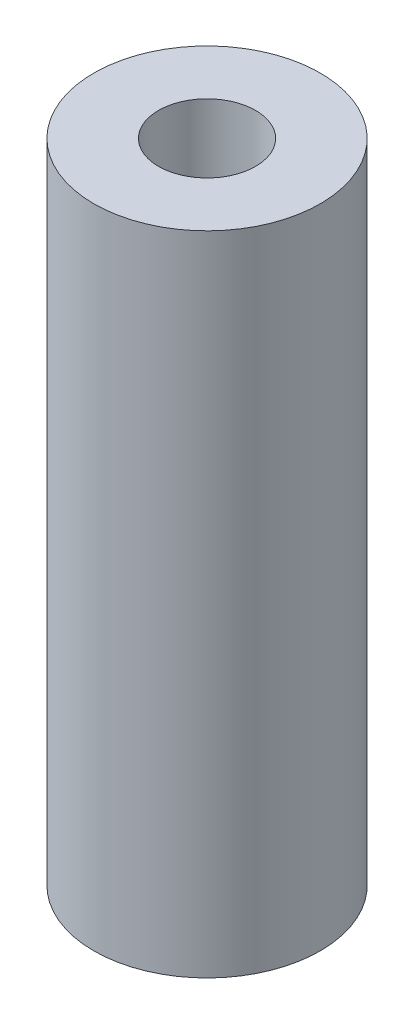
SolidWorks part; units mm, degrees
ref_plane "Front Plane" through (0, 0, 0) normal (0, 0, 1) x (1, 0, 0)
ref_plane "Top Plane" through (0, 0, 0) normal (0, 1, 0) x (1, 0, 0)
ref_plane "Right Plane" through (0, 0, 0) normal (1, 0, 0) x (0, 0, -1)
sketch "Sketch1" plane through (0, 0, 0) normal (0, 1, 0) x (1, 0, 0)
  circle A0 centre (0, 0) radius 3.5
  circle A1 centre (0, 0) radius 1.5
  dimension "D1" = 3
  dimension "D2" = 7
extrude "Boss-Extrude1" add sketch "Sketch1" along normal blind 20
